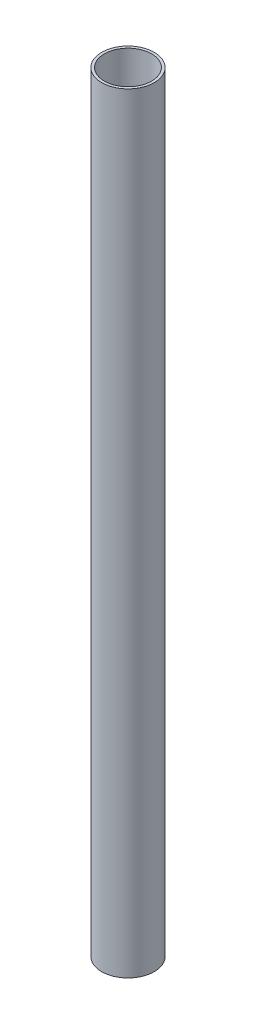
SolidWorks part; units mm, degrees
ref_plane "Front Plane" through (0, 0, 0) normal (0, 0, 1) x (1, 0, 0)
ref_plane "Top Plane" through (0, 0, 0) normal (0, 1, 0) x (1, 0, 0)
ref_plane "Right Plane" through (0, 0, 0) normal (1, 0, 0) x (0, 0, -1)
sketch "Sketch1" plane through (0, 0, 0) normal (0, 1, 0) x (1, 0, 0)
  circle A0 centre (0, 0) radius 18
  circle A1 centre (0, 0) radius 20
  dimension "D1" = 40
  dimension "D2" = 2
extrude "Boss-Extrude1" add sketch "Sketch1" along normal blind 586
